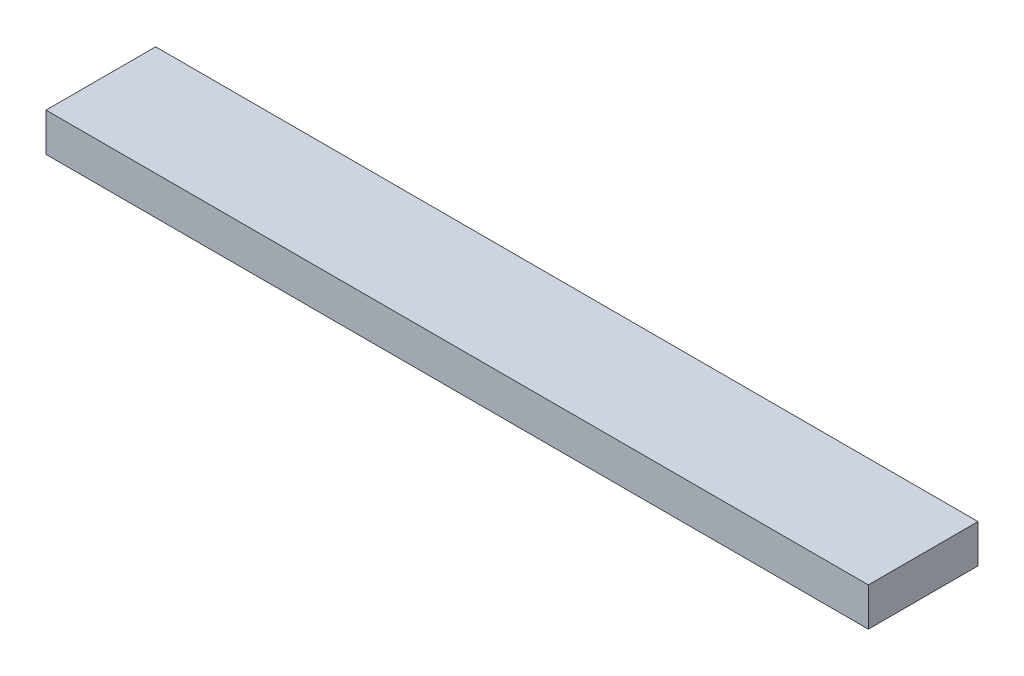
SolidWorks part; units mm, degrees
ref_plane "Front Plane" through (0, 0, 0) normal (0, 0, 1) x (1, 0, 0)
ref_plane "Top Plane" through (0, 0, 0) normal (0, 1, 0) x (1, 0, 0)
ref_plane "Right Plane" through (0, 0, 0) normal (1, 0, 0) x (0, 0, -1)
sketch "Sketch1" plane through (0, 0, 0) normal (0, 1, 0) x (1, 0, 0)
  line L1 (0, 0) -> (150, 0)
  line L2 (0, 0) -> (0, 20)
  line L3 (0, 20) -> (150, 20)
  line L4 (150, 0) -> (150, 20)
  dimension "D1" = 20
  dimension "D2" = 150
extrude "Boss-Extrude1" add sketch "Sketch1" along normal blind 7
